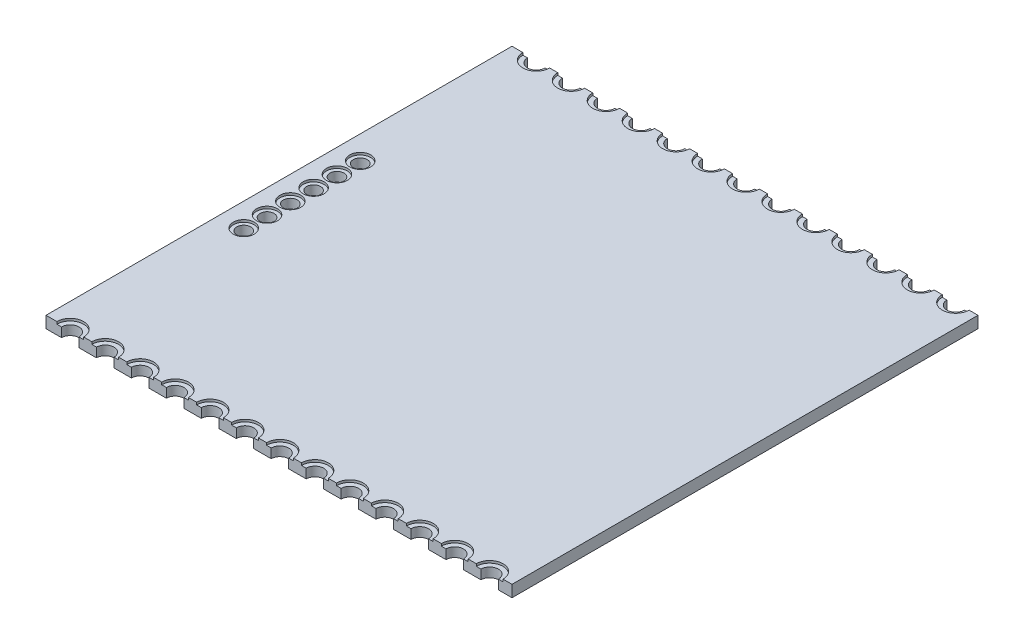
SolidWorks part; units mm, degrees
ref_plane "Ön Düzlem" through (0, 0, 0) normal (0, 0, 1) x (1, 0, 0)
ref_plane "Üst Düzlem" through (0, 0, 0) normal (0, 1, 0) x (1, 0, 0)
ref_plane "Sağ Düzlem" through (0, 0, 0) normal (1, 0, 0) x (0, 0, -1)
sketch "Çizim1" plane through (0, 0, 0) normal (0, 1, 0) x (1, 0, 0)
  line L1 (-20, -20) -> (20, -20)
  line L2 (-20, -20) -> (-20, 20)
  line L3 (-20, 20) -> (20, 20)
  line L4 (20, -20) -> (20, 20)
  line L5 (-20, -20) -> (20, 20) construction
  line L6 (-20, 20) -> (20, -20) construction
  point P0 (0, 0)
  dimension "D1" = 40
  dimension "D2" = 40
extrude "Yükseklik-Ekstrüzyon1" add sketch "Çizim1" along normal blind 1
sketch "Çizim2" plane through (0, 1, 1.3554) normal (0, 1, 0) x (1, 0, 0)
  line L0 (-17.99, 20) -> (-17.99, -20) construction
  circle A0 centre (-17.99, 6.3179) radius 0.5986
extrude "Kes-Ekstrüzyon1" cut sketch "Çizim2" against normal blind 2
pattern_linear "LÇoğaltma1" count 6 spacing 2 along (0, 0, 1) of "Kes-Ekstrüzyon1"
sketch "Çizim3" plane through (0, 1, 0) normal (0, 1, 0) x (1, 0, 0)
  circle A2 centre (-17.99, 4.9625) radius 0.8986
  circle A3 centre (-17.99, 4.9625) radius 0.8986
  dimension "D1" = 0.3
extrude "Kes-Ekstrüzyon2" cut sketch "Çizim3" against normal blind 0.2
pattern_linear "LÇoğaltma3" count 6 spacing 2 along (0, 0, 1) of "Kes-Ekstrüzyon2"
sketch "Çizim4" plane through (0, 1, 0) normal (0, 1, 0) x (1, 0, 0)
  line L0 (-20, -20) -> (20, -20) construction
  line L1 (-18.6676, -20) -> (-17.1676, -20)
  arc A0 (-18.6676, -20) -> (-17.1676, -20) centre (-17.9176, -20) cw
  point P3 (0, 0)
  point P6 (0, 0)
  dimension "D2" = 0.75
  dimension "D1" = 1.5
extrude "Kes-Ekstrüzyon3" cut sketch "Çizim4" against normal blind 1.2
sketch "Çizim5" plane through (0, 1, 0) normal (0, 1, 0) x (1, 0, 0)
  line L0 (-19.0676, -20) -> (-18.6676, -20)
  line L1 (-17.1676, -20) -> (-16.7676, -20)
  arc A2 (-16.7676, -20) -> (-19.0676, -20) centre (-17.9176, -20) ccw
  arc A3 (-16.7676, -20) -> (-19.0676, -20) centre (-17.9176, -20) ccw
  arc A4 (-18.6676, -20) -> (-17.1676, -20) centre (-17.9176, -20) cw
  dimension "D1" = 0.4
extrude "Kes-Ekstrüzyon4" cut sketch "Çizim5" against normal blind 0.2
pattern_linear "LÇoğaltma4" count 13 spacing 3 along (1, 0, 0) of "Kes-Ekstrüzyon3", "Kes-Ekstrüzyon4"
mirror "Aynalama1" about plane through (0, 0, 0) normal (0, 0, 1) of "LÇoğaltma4", "Kes-Ekstrüzyon3", "Kes-Ekstrüzyon4"
